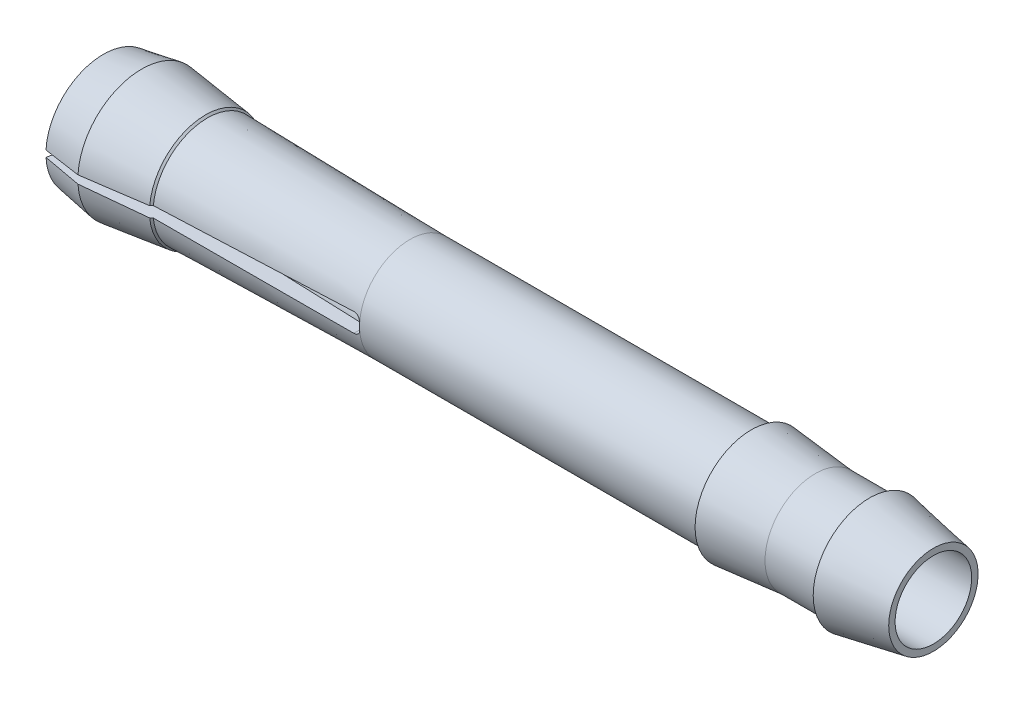
SolidWorks part; units mm, degrees
ref_plane "Plano frontal" through (0, 0, 0) normal (0, 0, 1) x (1, 0, 0)
ref_plane "Plano superior" through (0, 0, 0) normal (0, 1, 0) x (1, 0, 0)
ref_plane "Plano direito" through (0, 0, 0) normal (1, 0, 0) x (0, 0, -1)
sketch "Esboço1" plane through (0, 0, 0) normal (0, 0, 1) x (1, 0, 0)
  line L0 (0, 0) -> (25.6263, 0) construction
  line L1 (0.1333, 1) -> (0, 1.8)
  line L2 (0, 1.8) -> (1.2, 2)
  line L3 (1.2, 2) -> (3.2, 1.7564)
  line L4 (3.2, 1.7564) -> (3.2564, 1.7)
  line L5 (3.2564, 1.7) -> (9.6, 1.575)
  line L6 (9.6, 1.575) -> (20.3, 1.575)
  line L7 (26, 1.4) -> (26, 1.2)
  line L8 (24, 1.765) -> (24, 1.575)
  line L9 (26, 1.2) -> (9.6, 1.2)
  line L10 (24, 1.765) -> (26, 1.4)
  line L11 (22.3, 1.575) -> (20.3, 1.765)
  line L12 (20.3, 1.765) -> (20.3, 1.575)
  line L13 (22.3, 1.575) -> (24, 1.575)
  line L14 (0.1333, 1) -> (9.6, 1.2)
  dimension "D1" = 3.15
  dimension "D2" = 1.2
  dimension "D3" = 4
  dimension "D4" = 45
  dimension "D5" = 3.2
  dimension "D6" = 9.6
  dimension "D7" = 3.4
  dimension "D8" = 26
  dimension "D9" = 1.8
  dimension "D10" = 2.4
  dimension "D11" = 3.53
  dimension "D12" = 2
  dimension "D13" = 0.2
  dimension "D14" = 2.8
  dimension "D15" = 2
  dimension "D16" = 3.53
  dimension "D17" = 1.7
  dimension "D18" = 1.129
  dimension "D19" = 2
revolve "Revolução1" add sketch "Esboço1" angle 360 about L0
sketch "Esboço2" plane through (0, 0, 0) normal (0, 0, 1) x (1, 0, 0)
  line L0 (9.6, 1.575) -> (9.6, -1.575) construction
  line L1 (0, 0.1) -> (9.3958, 0.2957)
  line L2 (0, 1.8) -> (0, -1.8) construction
  line L3 (0, -0.1) -> (9.3958, -0.2957)
  line L4 (9.6, 0.0958) -> (9.6, -0.0958)
  line L6 (0, 0) -> (11.1097, 0) construction
  line L7 (0, 0.1) -> (0, -0.1)
  arc A0 (9.3958, -0.2957) -> (9.6, -0.0958) centre (9.4, -0.0958) ccw
  arc A1 (9.6, 0.0958) -> (9.3958, 0.2957) centre (9.4, 0.0958) ccw
  point P13 (9.6, -0.3)
  point P16 (9.6, 0.3)
  dimension "D3" = 0.2
  dimension "D1" = 0.6
  dimension "D2" = 0.2
extrude "Corte-extrusão1" cut sketch "Esboço2" against normal mid plane 10
sketch "Esboço3" plane through (0, 0, 0) normal (0, 0, 1) x (1, 0, 0)
  line L0 (0, 0) -> (-5.5, 0) construction
  line L1 (-5.5, 1.8) -> (-5.5, -1.8)
  line L2 (-5.5, 1.8) -> (-4.3, 2)
  line L3 (1.2, 2) -> (0, 1.8) construction
  line L4 (-5.5, -1.8) -> (-4.3, -2)
  line L5 (-4.3, 2) -> (-2.501, 1.7809)
  line L6 (3.2, 1.7564) -> (1.2, 2) construction
  line L7 (-4.3, -2) -> (-2.501, -1.7809)
  dimension "D1" = 5.5
